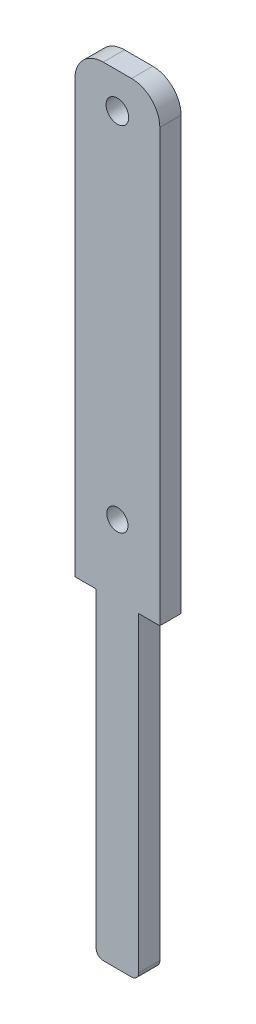
SolidWorks part; units mm, degrees
ref_plane "Alzado" through (0, 0, 0) normal (0, 0, 1) x (1, 0, 0)
ref_plane "Planta" through (0, 0, 0) normal (0, 1, 0) x (1, 0, 0)
ref_plane "Vista lateral" through (0, 0, 0) normal (1, 0, 0) x (0, 0, -1)
sketch "Croquis1" plane through (0, 0, 0) normal (0, 0, 1) x (1, 0, 0)
  line L0 (-6, -10) -> (-3, -10)
  line L1 (-6, -55) -> (6, -55)
  line L2 (-6, -55) -> (-6, 51)
  line L3 (-2, 55) -> (2, 55)
  line L4 (6, -55) -> (6, 51)
  line L5 (-6, -55) -> (6, 55) construction
  line L6 (-6, 55) -> (6, -55) construction
  line L7 (-3, -10) -> (-3, -55)
  line L8 (-3, -55) -> (3, -55)
  line L9 (3, -55) -> (3, -10)
  line L10 (3, -10) -> (6, -10)
  line L11 (0, 7.2736) -> (0, -54.5813) construction
  arc A0 (2, 55) -> (6, 51) centre (2, 51) cw
  arc A1 (-6, 51) -> (-2, 55) centre (-2, 51) cw
  point P0 (0, 0)
  dimension "D3" = 4
  dimension "D1" = 12
  dimension "D2" = 110
  dimension "D4" = 6
  dimension "D5" = 10
extrude "Saliente-Extruir1" add sketch "Croquis1" along normal mid plane 3 contours A1 L2 L0 L7 L1 L9 L10 L4 A0 L3
sketch "Croquis2" plane through (0, 0, 1.5) normal (0, 0, 1) x (1, 0, 0)
  line L0 (0, 0) -> (0, 30.7504) construction
  line L1 (-2, 55) -> (2, 55) construction
  circle A0 centre (0, 50) radius 1.6
  dimension "D2" = 3.2
  dimension "D1" = 5
extrude "Cortar-Extruir1" cut sketch "Croquis2" against normal blind 3
fillet "Redondeo1" radius 1 2 edges at (3, -55, 0) (-3, -55, 0)
sketch "Croquis3" plane through (0, 0, 0) normal (0, 0, 1) x (1, 0, 0)
  line L0 (10.7818, 0) -> (-13.2209, 0) construction
  circle A0 centre (0, 0) radius 1.5
  dimension "D1" = 3
extrude "Cortar-Extruir2" cut sketch "Croquis3" against normal mid plane 10
